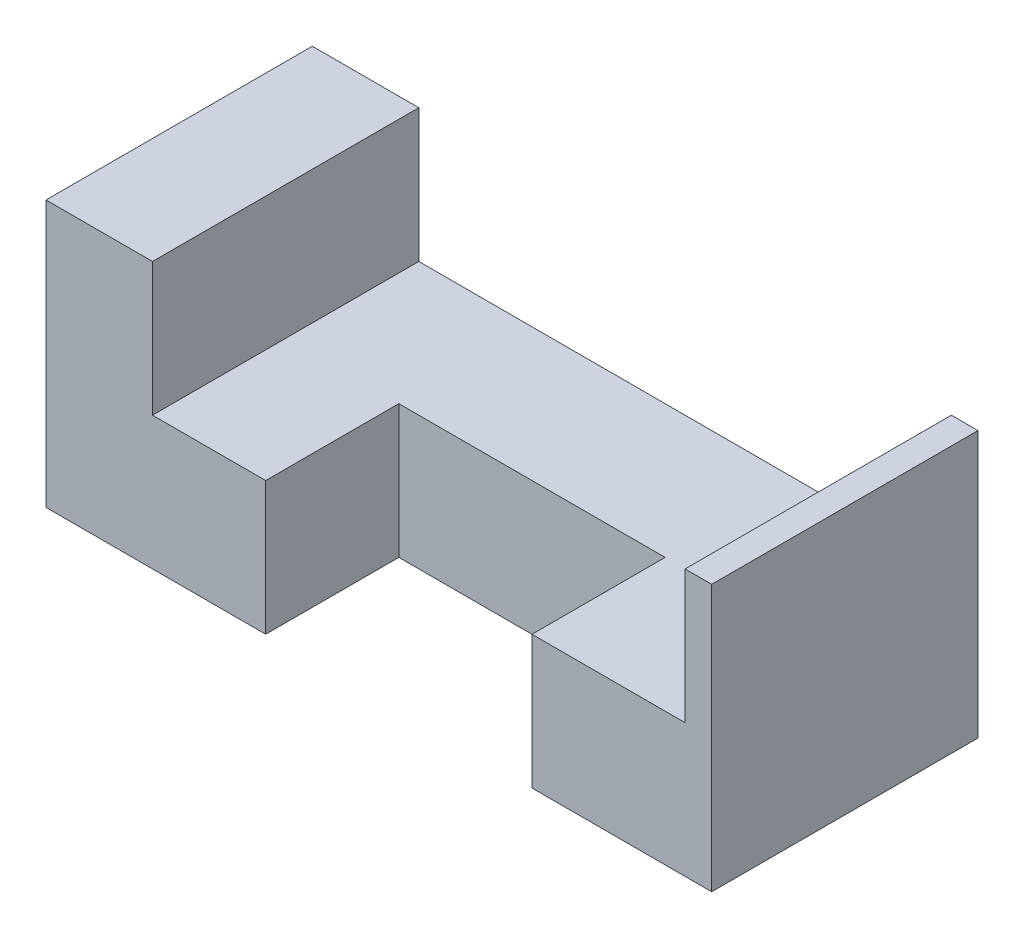
SolidWorks part; units mm, degrees
ref_plane "前基準面" through (0, 0, 0) normal (0, 0, 1) x (1, 0, 0)
ref_plane "上基準面" through (0, 0, 0) normal (0, 1, 0) x (1, 0, 0)
ref_plane "右基準面" through (0, 0, 0) normal (1, 0, 0) x (0, 0, -1)
sketch "草圖1" plane through (0, 0, 0) normal (0, 0, 1) x (1, 0, 0)
  line L1 (-25, 10) -> (25, 10)
  line L2 (-25, 10) -> (-25, -10)
  line L3 (-25, -10) -> (25, -10)
  line L4 (25, 10) -> (25, -10)
  line L5 (-25, 10) -> (25, -10) construction
  line L6 (-25, -10) -> (25, 10) construction
  line L7 (-17, 10) -> (23, 10)
  line L8 (-17, 10) -> (-17, 0)
  line L9 (-17, 0) -> (23, 0)
  line L10 (23, 10) -> (23, 0)
  point P0 (0, 0)
  point P10 (0, 0)
  point P11 (0, 0)
  point P12 (16.5292, 12.8675)
  dimension "D1" = 50
  dimension "D2" = 20
  dimension "D3" = 10
  dimension "D4" = 2
  dimension "D5" = 40
extrude "填料-伸長1" add sketch "草圖1" along normal blind 20 contours L1 L10 L9 L8 L2 L3 L4
sketch "草圖2" plane through (0, 0, 0) normal (0, 1, 0) x (1, 0, 0)
  line L0 (-17, -20) -> (23, -20) construction
  line L1 (11.5, -20) -> (-8.5, -20)
  line L2 (11.5, -20) -> (11.5, -10)
  line L3 (11.5, -10) -> (-8.5, -10)
  line L4 (-8.5, -20) -> (-8.5, -10)
  dimension "D1" = 11.5
  dimension "D2" = 8.5
  dimension "D3" = 10
extrude "除料-伸長1" cut sketch "草圖2" against normal blind 10
